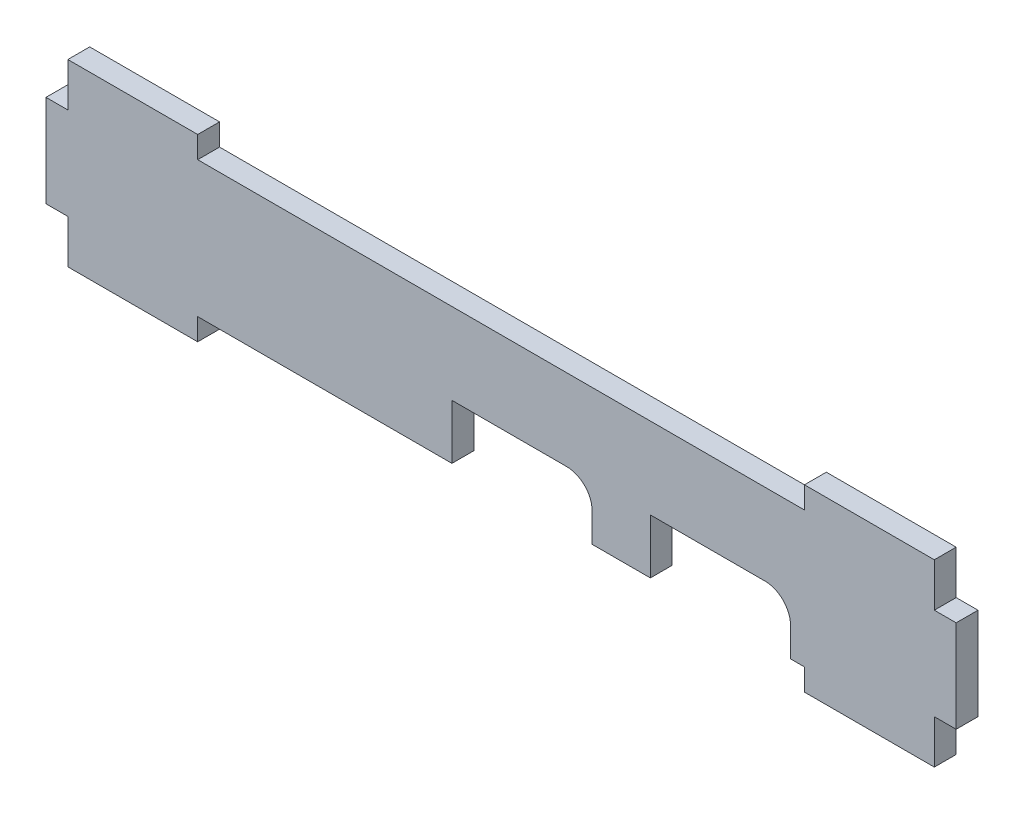
SolidWorks part; units mm, degrees
ref_plane "Front Plane" through (0, 0, 0) normal (0, 0, 1) x (1, 0, 0)
ref_plane "Top Plane" through (0, 0, 0) normal (0, 1, 0) x (1, 0, 0)
ref_plane "Right Plane" through (0, 0, 0) normal (1, 0, 0) x (0, 0, -1)
sketch "Sketch1" plane through (0, 0, 0) normal (0, 0, 1) x (1, 0, 0)
  line L1 (0, 0) -> (500, 0)
  line L2 (0, 0) -> (0, 98.65)
  line L3 (0, 98.65) -> (500, 98.65)
  line L4 (500, 0) -> (500, 98.65)
  dimension "D1" = 500
  dimension "D2" = 98.65
extrude "Boss-Extrude1" add sketch "Sketch1" along normal blind 12
sketch "Sketch2" plane through (0, 0, 12) normal (0, 0, 1) x (1, 0, 0)
  line L0 (500, 98.65) -> (0, 98.65) construction
  line L1 (500, 98.65) -> (488, 98.65)
  line L2 (500, 98.65) -> (500, 74.65)
  line L3 (500, 74.65) -> (488, 74.65)
  line L4 (488, 98.65) -> (488, 74.65)
  line L5 (500, 0) -> (488, 0)
  line L6 (500, 0) -> (500, 24)
  line L7 (500, 24) -> (488, 24)
  line L8 (488, 0) -> (488, 24)
  line L9 (0, 0) -> (12, 0)
  line L10 (0, 0) -> (0, 24)
  line L11 (0, 24) -> (12, 24)
  line L12 (12, 0) -> (12, 24)
  line L13 (0, 98.65) -> (12, 98.65)
  line L14 (0, 98.65) -> (0, 74.65)
  line L15 (0, 74.65) -> (12, 74.65)
  line L16 (12, 98.65) -> (12, 74.65)
  line L17 (83.3333, 98.65) -> (416.6667, 98.65)
  line L18 (83.3333, 98.65) -> (83.3333, 86.65)
  line L19 (83.3333, 86.65) -> (416.6667, 86.65)
  line L20 (416.6667, 98.65) -> (416.6667, 86.65)
  line L21 (0, 98.65) -> (0, 0) construction
  line L22 (0, 0) -> (500, 0) construction
  line L23 (83.3333, 0) -> (416.6667, 0)
  line L24 (83.3333, 0) -> (83.3333, 12)
  line L25 (83.3333, 12) -> (416.6667, 12)
  line L26 (416.6667, 0) -> (416.6667, 12)
  point P26 (250, 98.65)
  dimension "D1" = 12
  dimension "D2" = 24
  dimension "D3" = 12
  dimension "D4" = 24
  dimension "D5" = 24
  dimension "D6" = 12
  dimension "D7" = 12
  dimension "D8" = 24
  dimension "D9" = 333.3333
  dimension "D10" = 250
  dimension "D11" = 83.3333
extrude "Cut-Extrude1" cut sketch "Sketch2" against normal through all
scale "Scale1" scale about centroid uniform scaling yes scale factor 0.5
sketch "Sketch3" plane through (0, 0, 9) normal (0, 0, 1) x (1, 0, 0)
  line L0 (333.3333, 30.6625) -> (166.6667, 30.6625) construction
  line L1 (329.5033, 30.6625) -> (291.0033, 30.6625)
  line L2 (329.5033, 30.6625) -> (329.5033, 45.6625)
  line L3 (329.5033, 45.6625) -> (291.0033, 45.6625)
  line L4 (291.0033, 30.6625) -> (291.0033, 45.6625)
  line L5 (275.0033, 30.6625) -> (236.5033, 30.6625)
  line L6 (275.0033, 30.6625) -> (275.0033, 45.6625)
  line L7 (275.0033, 45.6625) -> (236.5033, 45.6625)
  line L8 (236.5033, 30.6625) -> (236.5033, 45.6625)
  line L10 (333.3333, 24.6625) -> (333.3333, 30.6625) construction
  dimension "D1" = 15
  dimension "D2" = 38.5
  dimension "D3" = 16
  dimension "D4" = 0
  dimension "D5" = 3.83
  dimension "D6" = 15
  dimension "D7" = 0
extrude "Cut-Extrude2" cut sketch "Sketch3" against normal through all
fillet "Fillet1" radius 7 2 edges at (275.0033, 45.6625, 6) (329.5033, 45.6625, 6)
